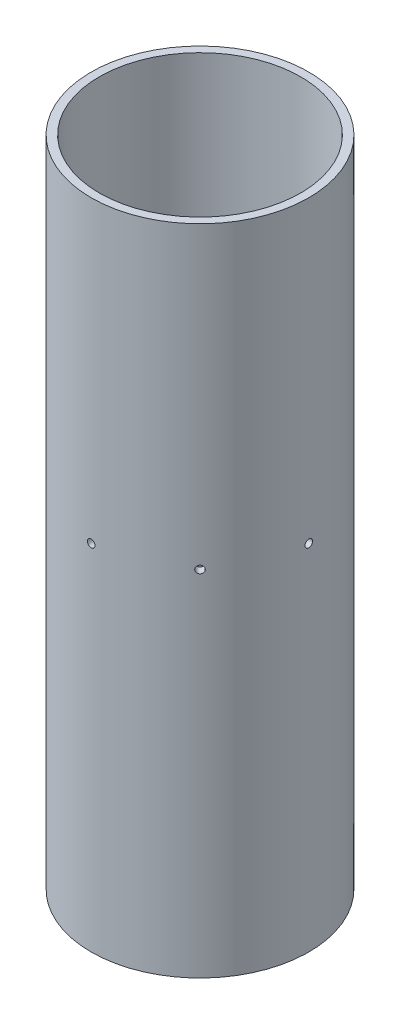
SolidWorks part; units mm, degrees
ref_plane "Front Plane" through (0, 0, 0) normal (0, 0, 1) x (1, 0, 0)
ref_plane "Top Plane" through (0, 0, 0) normal (0, 1, 0) x (1, 0, 0)
ref_plane "Right Plane" through (0, 0, 0) normal (1, 0, 0) x (0, 0, -1)
sketch "Sketch2" plane through (0, 0, 0) normal (0, 1, 0) x (1, 0, 0)
  circle A0 centre (0, 0) radius 50.8
  circle A1 centre (0, 0) radius 46.99
  dimension "D1" = 101.6
  dimension "D2" = 93.98
extrude "Coupler Extrusion" add sketch "Sketch2" along normal blind 304.8
ref_plane "Plane1" through (0, 0, 50.8) normal (0, 0, 1) x (1, 0, 0)
sketch "Sketch3" plane through (0, 0, 50.8) normal (0, 0, 1) x (1, 0, 0)
  line L0 (0, 304.8) -> (0, 0) construction
  line L1 (46.99, 304.8) -> (-46.99, 304.8) construction
  line L2 (-46.99, 0) -> (46.99, 0) construction
  circle A0 centre (0, 165.1) radius 1.7526
  dimension "D1" = 165.1
  dimension "D2" = 3.5052
extrude "Bulkhead Holes" cut sketch "Sketch3" against normal up to next
pattern_circular "CirPattern1" count 8 over 360 about axis through (0, 304.8, 0) along (0, -1, 0) of "Bulkhead Holes"
